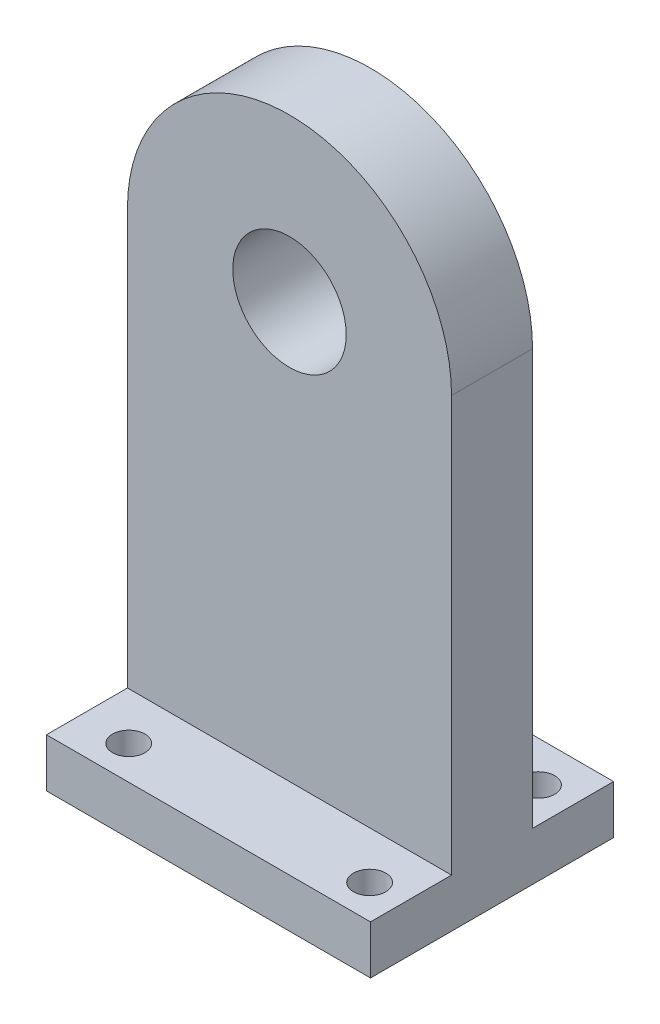
SolidWorks part; units mm, degrees
ref_plane "Plan de face" through (0, 0, 0) normal (0, 0, 1) x (1, 0, 0)
ref_plane "Plan de dessus" through (0, 0, 0) normal (0, 1, 0) x (1, 0, 0)
ref_plane "Plan de droite" through (0, 0, 0) normal (1, 0, 0) x (0, 0, -1)
sketch "Esquisse1" plane through (0, 0, 0) normal (0, 0, 1) x (1, 0, 0)
  line L0 (-10, -28.63) -> (-10, 0)
  line L1 (10, 0) -> (10, -28.63)
  line L2 (10, -28.63) -> (-10, -28.63)
  arc A0 (-10, 0) -> (10, 0) centre (0, 0) cw
  point P4 (0, 0)
  dimension "D2" = 28.63
  dimension "D1" = 20
extrude "Boss.-Extru.1" add sketch "Esquisse1" along normal blind 5
sketch "Esquisse2" plane through (0, 0, 5) normal (0, 0, 1) x (1, 0, 0)
  circle A0 centre (0, 0) radius 3.5
  dimension "D1" = 7
extrude "Enlèv. mat.-Extru.1" cut sketch "Esquisse2" against normal blind 5
sketch "Esquisse3" plane through (0, 0, 5) normal (0, 0, 1) x (1, 0, 0)
  line L0 (10, -28.63) -> (10, 0) construction
  line L1 (-10, -28.63) -> (10, -28.63)
  line L2 (-10, -28.63) -> (-10, -25.63)
  line L3 (-10, -25.63) -> (10, -25.63)
  line L4 (10, -28.63) -> (10, -25.63)
  dimension "D1" = 3
extrude "Boss.-Extru.2" add sketch "Esquisse3" along normal blind 5 and the other way blind 10
sketch "Esquisse4" plane through (0, -25.63, 0) normal (0, 1, 0) x (1, 0, 0)
  line L0 (-10, 5) -> (-10, 0) construction
  line L1 (10, 5) -> (-10, 5) construction
  circle A0 centre (-7, -7.9207) radius 1
  circle A1 centre (7.8654, -7.9207) radius 1
  circle A2 centre (7.8654, 2.5) radius 1
  circle A4 centre (-7, 2.5) radius 1
  point P8 (0, 0)
  point P9 (0, 0)
  point P10 (0, 0)
  point P11 (0, 0)
  dimension "D1" = 2
  dimension "D2" = 3
  dimension "D3" = 2.5
extrude "Enlèv. mat.-Extru.2" cut sketch "Esquisse4" against normal blind 5
